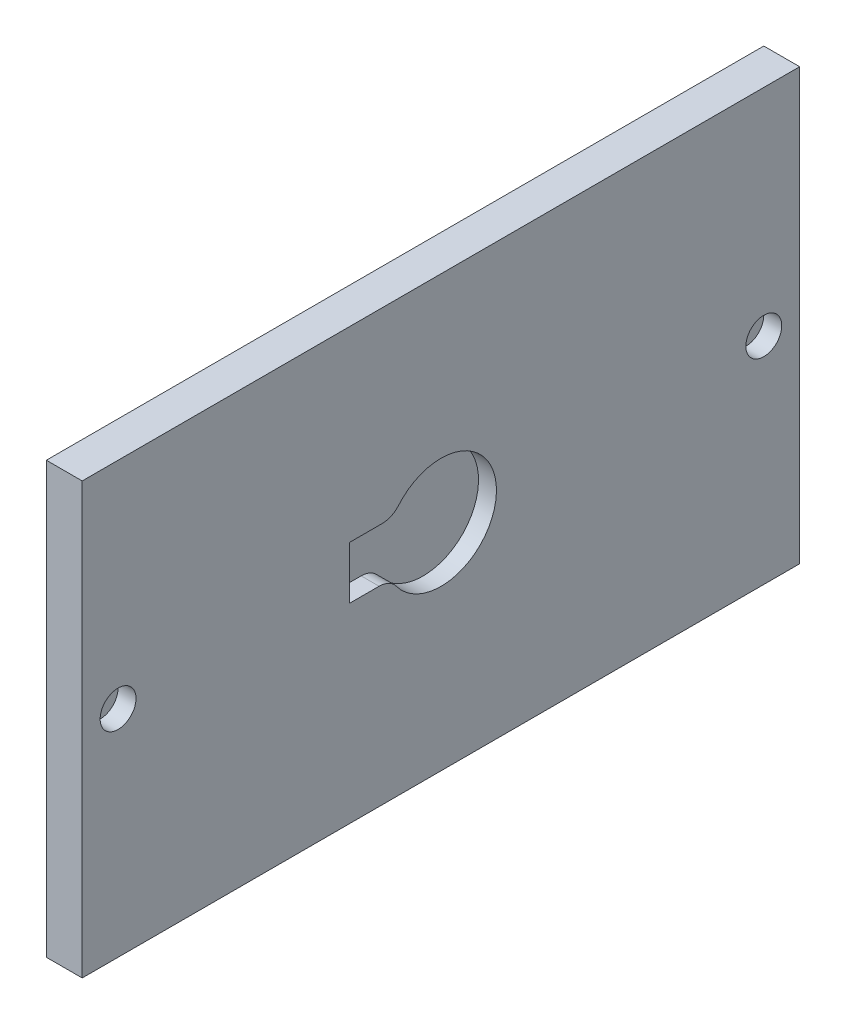
SolidWorks part; units mm, degrees
ref_plane "Front Plane" through (0, 0, 0) normal (0, 0, 1) x (1, 0, 0)
ref_plane "Top Plane" through (0, 0, 0) normal (0, 1, 0) x (1, 0, 0)
ref_plane "Right Plane" through (0, 0, 0) normal (1, 0, 0) x (0, 0, -1)
sketch "Sketch1" plane through (0, 0, 0) normal (1, 0, 0) x (0, 0, -1)
  line L1 (127, -76.2) -> (-127, -76.2)
  line L2 (127, -76.2) -> (127, 76.2)
  line L3 (127, 76.2) -> (-127, 76.2)
  line L4 (-127, -76.2) -> (-127, 76.2)
  line L5 (127, -76.2) -> (-127, 76.2) construction
  line L6 (127, 76.2) -> (-127, -76.2) construction
  point P0 (0, 0)
  dimension "D1" = 254
  dimension "D2" = 152.4
extrude "Boss-Extrude1" add sketch "Sketch1" along normal blind 12.7
sketch "Sketch2" plane through (12.7, 0, 0) normal (1, 0, 0) x (0, 0, -1)
  line L0 (0, 0) -> (101.6, 0) construction
  line L2 (0, 0) -> (131.9823, 76.2) construction
  line L3 (127, 76.2) -> (-127, 76.2) construction
  line L4 (-127, -76.2) -> (127, -76.2) construction
  circle A0 centre (65.1684, 37.625) radius 6.4897
  circle A1 centre (86.8201, 50.1256) radius 5.3581
  point P0 (0, 0)
  dimension "D3" = 12.9794
  dimension "D4" = 10.7163
  dimension "D1" = 30
  dimension "D2" = 75.25
  dimension "D5" = 25.0012
  dimension "D6" = 76.2
extrude "Cut-Extrude1" [suppressed] cut sketch "Sketch2" against normal through all
sketch "Sketch3" plane through (12.7, 0, 0) normal (1, 0, 0) x (0, 0, -1)
  line L0 (127, -76.2) -> (127, 76.2) construction
  line L1 (-127, 76.2) -> (-127, -76.2) construction
  circle A0 centre (114.3, 0) radius 6.35
  circle A1 centre (-114.3, 0) radius 6.35
  dimension "D1" = 12.7
  dimension "D2" = 12.7
  dimension "D3" = 12.7
  dimension "D4" = 12.7
extrude "Cut-Extrude2" cut sketch "Sketch3" against normal blind 6.35
hole_wizard "1/4 (0.25) Diameter Hole1" positions "Sketch4" profile "Sketch6" hole size "1/4" standard "ANSI Inch"
sketch "Sketch4" plane through (0, -76.2, 0) normal (0, -1, 0) x (-1, 0, 0)
  line L0 (-12.7, -127) -> (0, -127) construction
  line L1 (-12.7, 127) -> (0, 127) construction
  point P0 (-6.2363, -114.3)
  point P2 (-6.2363, 0)
  point P4 (-6.2363, 114.3)
  dimension "D1" = 12.7
  dimension "D2" = 12.7
  dimension "D3" = 127
sketch "Sketch6" plane through (6.2363, -76.2, 114.3) normal (1, 0, 0) x (0, 0, -1)
  line L0 (0, 0) -> (0, 14.6077)
  line L1 (0, 14.6077) -> (3.175, 12.7)
  line L2 (3.175, 12.7) -> (3.175, 0)
  line L5 (3.175, 0) -> (0, 0)
  line L10 (0, 14.6077) -> (-3.175, 12.7) construction
  line L11 (0, -6.35) -> (0, 107.95) construction
  dimension "Hole Dia." = 6.35
  dimension "Hole Depth" = 12.7
  dimension "Drill Angle" = 118
sketch "Sketch7" plane through (12.7, 0, 0) normal (1, 0, 0) x (0, 0, -1)
  line L5 (19.05, -4.826) -> (-19.05, 4.826) construction
  line L6 (19.05, 4.826) -> (-19.05, -4.826) construction
  line L7 (0, -8.635) -> (-32.3247, -8.635)
  line L8 (0, -8.635) -> (0, 10.0329)
  line L9 (0, 10.0329) -> (-32.3247, 10.0329)
  line L10 (-32.3247, -8.635) -> (-32.3247, 10.0329)
  circle A0 centre (0, 0) radius 19.6518
  point P0 (0, 0)
  dimension "D1" = 38.1
  dimension "D2" = 9.652
extrude "Cut-Extrude3" cut sketch "Sketch7" against normal blind 6.35 contours L7 A0 L9 L8 | L9 A0 L7 L8 | A0 L9 L10 L7
fillet "Fillet1" radius 7.62 2 edges at (9.525, -8.635, 17.6531) (9.525, 10.0329, 16.8978)
